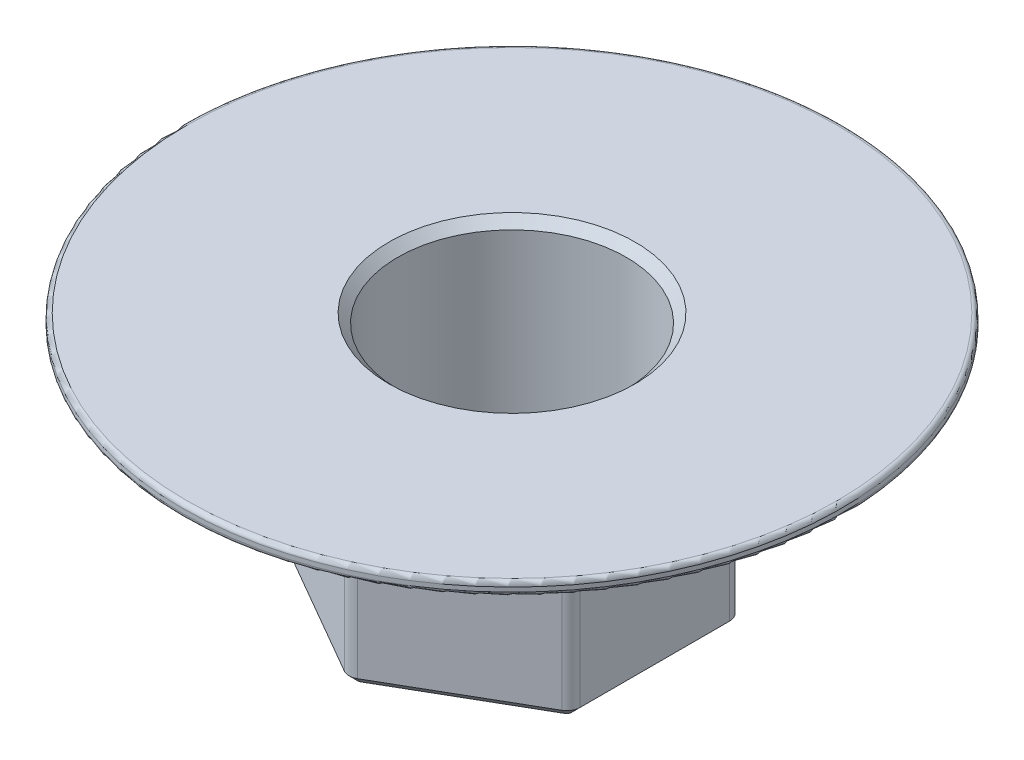
SolidWorks part; units mm, degrees
ref_plane "Front Plane" through (0, 0, 0) normal (0, 0, 1) x (1, 0, 0)
ref_plane "Top Plane" through (0, 0, 0) normal (0, 1, 0) x (1, 0, 0)
ref_plane "Right Plane" through (0, 0, 0) normal (1, 0, 0) x (0, 0, -1)
sketch "Sketch2" plane through (0, 0, 0) normal (0, 1, 0) x (1, 0, 0)
  circle A0 centre (0, 0) radius 75
  circle A1 centre (0, 0) radius 26
  dimension "D1" = 52
  dimension "D2" = 150
extrude "Boss-Extrude1" add sketch "Sketch2" along normal blind 55
sketch "Sketch3" plane through (0, 0, 0) normal (0, -1, 0) x (1, 0, 0)
  line L1 (32.5, -18.7639) -> (32.5, 18.7639)
  line L2 (32.5, 18.7639) -> (0, 37.5278)
  line L3 (0, 37.5278) -> (-32.5, 18.7639)
  line L4 (-32.5, 18.7639) -> (-32.5, -18.7639)
  line L5 (-32.5, -18.7639) -> (0, -37.5278)
  line L6 (0, -37.5278) -> (32.5, -18.7639)
  circle A0 centre (0, 0) radius 75 construction
  circle A1 centre (0, 0) radius 75
  circle A3 centre (0, 0) radius 32.5 construction
  dimension "D1" = 65
extrude "Cut-Extrude1" cut sketch "Sketch3" against normal offset from surface 3 and the other way through all up to face at (0, 55, 75)
fillet "Fillet1" radius 3 6 edges at (32.5, 26, -18.7639) (32.5, 26, 18.7639) (0, 26, 37.5278) (-32.5, 26, 18.7639) (-32.5, 26, -18.7639) (0, 26, -37.5278)
chamfer "Chamfer1" distance 2 angle 45 12 edges at (0, 0, -37.0637) (-16.25, 0, -28.1458) (-32.0981, 0, -18.5318) (-32.5, 0, 0) (-32.0981, 0, 18.5318) (-16.25, 0, 28.1458) (0, 0, 37.0637) (16.25, 0, 28.1458) (32.0981, 0, 18.5318) (32.5, 0, 0) (32.0981, 0, -18.5318) (16.25, 0, -28.1458)
chamfer "Chamfer3" distance 2 angle 45 1 edges at (0, 55, 26)
fillet "Fillet2" radius 1 2 edges at (0, 52, 75) (0, 55, 75)
